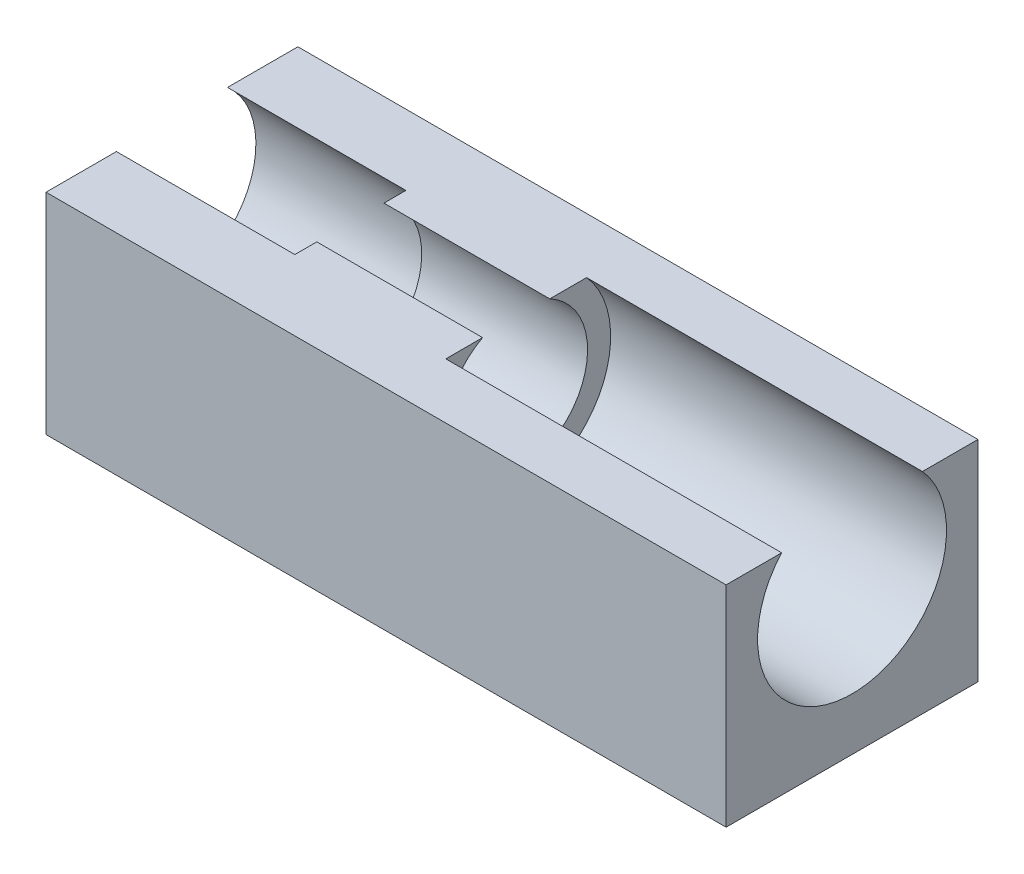
SolidWorks part; units mm, degrees
ref_plane "前基準面" through (0, 0, 0) normal (0, 0, 1) x (1, 0, 0)
ref_plane "上基準面" through (0, 0, 0) normal (0, 1, 0) x (1, 0, 0)
ref_plane "右基準面" through (0, 0, 0) normal (1, 0, 0) x (0, 0, -1)
sketch "草圖1" plane through (0, 0, 0) normal (0, 1, 0) x (1, 0, 0)
  line L1 (-16.2, 6) -> (16.2, 6)
  line L2 (-16.2, 6) -> (-16.2, -6)
  line L3 (-16.2, -6) -> (16.2, -6)
  line L4 (16.2, 6) -> (16.2, -6)
  line L5 (-16.2, 6) -> (16.2, -6) construction
  line L6 (-16.2, -6) -> (16.2, 6) construction
  point P0 (0, 0)
  dimension "D1" = 32.4
  dimension "D2" = 12
extrude "填料-伸長1" add sketch "草圖1" along normal blind 10
sketch "草圖3" plane through (-16.2, 0, 0) normal (-1, 0, 0) x (0, 0, 1)
  line L0 (0, -1000) -> (0, 49000) construction
  line L1 (-6, 10) -> (6, 10) construction
  line L2 (0, 10) -> (-1.142, 10) construction
  line L3 (0, 10) -> (0, 7) construction
  line L4 (0, 7) -> (-1.142, 7) construction
  line L5 (-1.142, 10) -> (-1.142, 7) construction
  line L6 (-1001.142, 7) -> (48998.858, 7) construction
  dimension "D1" = 3
sketch "草圖4" plane through (-16.2, 0, 0) normal (-1, 0, 0) x (0, 0, 1)
  circle A0 centre (0, 7) radius 4
  dimension "D1" = 8
extrude "除料-伸長2" cut sketch "草圖4" against normal blind 8.5
ref_plane "平面2" through (-16.2, 0, 0) normal (-1, 0, 0) x (0, 0, 1)
sketch "草圖6" plane through (-16.2, 0, 0) normal (-1, 0, 0) x (0, 0, 1)
  circle A0 centre (0, 7) radius 4
curve "螺旋曲線/渦捲線2" pitch 0.4054 height 8.5135 turns 21
sketch "草圖7" plane through (-7.7, 0, 0) normal (-1, 0, 0) x (0, 0, 1)
  circle A0 centre (0, 7) radius 3.4
  dimension "D1" = 6.8
extrude "除料-伸長3" cut sketch "草圖7" against normal blind 7.9
sketch "草圖8" plane through (16.2, 0, 0) normal (1, 0, 0) x (0, 0, -1)
  circle A0 centre (0, 7) radius 4.5
  dimension "D1" = 9
extrude "除料-伸長4" cut sketch "草圖8" against normal blind 16
